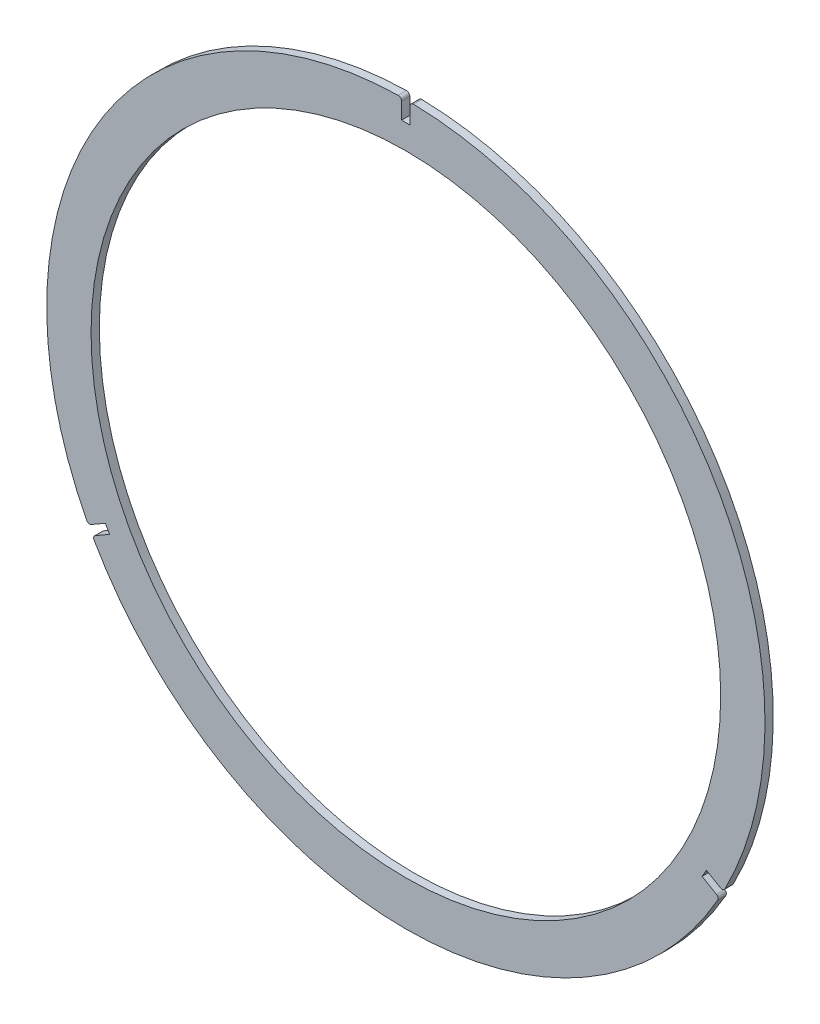
SolidWorks part; units mm, degrees
material "Balsa"
ref_plane "Front Plane" through (0, 0, 0) normal (0, 0, 1) x (1, 0, 0)
ref_plane "Top Plane" through (0, 0, 0) normal (0, 1, 0) x (1, 0, 0)
ref_plane "Right Plane" through (0, 0, 0) normal (1, 0, 0) x (0, 0, -1)
sketch "Sketch1" plane through (0, 0, 0) normal (0, 0, 1) x (1, 0, 0)
  line L0 (0, 0) -> (0, 499.9473) construction
  line L1 (0, -114.7984) -> (0, -129.4545) construction
  line L2 (0, -374.4718) -> (0, 404.2655) construction
  line L3 (-1.651, 142.9921) -> (-1.651, 150.6121)
  line L4 (1.651, 142.9921) -> (1.651, 150.6121)
  line L5 (-1.651, 142.9921) -> (1.651, 142.9921)
  line L6 (136.2041, -53.806) -> (0.0002, 24.7625) construction
  line L7 (-136.2076, -53.7991) -> (0.0002, 24.7625) construction
  line L8 (136.2041, -53.806) -> (0.0002, 24.7625) construction
  line L9 (-136.2076, -53.7991) -> (0.0002, 24.7625) construction
  line L10 (-125.0584, -45.4626) -> (-118.4576, -41.6554) construction
  line L11 (-123.6259, -48.4483) -> (-116.8078, -44.5157) construction
  line L12 (-118.4576, -41.6554) -> (-116.8078, -44.5157) construction
  line L13 (-124.1455, -48.7479) -> (-123.6847, -48.4822) construction
  line L14 (-123.6847, -48.4822) -> (-123.6259, -48.4483) construction
  line L15 (-125.7952, -45.8876) -> (-125.1113, -45.4931) construction
  line L16 (-125.1113, -45.4931) -> (-125.0584, -45.4626) construction
  line L17 (125.4797, -45.7137) -> (125.1075, -45.499) construction
  line L18 (123.8298, -48.5739) -> (123.6807, -48.488) construction
  line L19 (117.0223, -44.647) -> (118.6722, -41.7868) construction
  line L20 (123.6807, -48.488) -> (123.6228, -48.4545) construction
  line L21 (123.6228, -48.4545) -> (117.0223, -44.647) construction
  line L22 (125.1075, -45.499) -> (125.0554, -45.4689) construction
  line L23 (125.0554, -45.4689) -> (118.6722, -41.7868) construction
  line L24 (-115.3206, -47.981) -> (-121.8597, -51.7592)
  line L25 (-113.7312, -50.732) -> (-120.2754, -54.5131)
  line L26 (-113.7312, -50.732) -> (-120.2754, -54.5131) construction
  line L27 (-115.3206, -47.981) -> (-121.8597, -51.7592) construction
  line L28 (-115.4206, -47.9666) -> (-121.9445, -51.7361)
  line L29 (-120.2754, -54.5131) -> (-115.3206, -47.981) construction
  line L30 (-117.798, -51.2471) -> (-122.1124, -53.7399) construction
  line L31 (-113.7686, -50.8257) -> (-120.3665, -54.6379)
  line L32 (-115.4206, -47.9666) -> (-113.7686, -50.8257)
  line L33 (113.7316, -50.7396) -> (129.9098, -60.0883)
  line L34 (115.3212, -47.9888) -> (131.505, -57.3407)
  line L35 (129.9098, -60.0883) -> (131.505, -57.3407)
  line L36 (129.9098, -60.0883) -> (131.505, -57.3407) construction
  line L37 (115.3212, -47.9888) -> (131.505, -57.3407) construction
  line L38 (113.7316, -50.7396) -> (129.9098, -60.0883) construction
  line L39 (129.9098, -60.0883) -> (115.3212, -47.9888) construction
  line L40 (122.6155, -54.0385) -> (101.8722, -42.0519) construction
  line L41 (120.3631, -54.6438) -> (113.7655, -50.8313)
  line L42 (122.0152, -51.7848) -> (122.0057, -51.7794) construction
  line L43 (113.7655, -50.8313) -> (115.4176, -47.9723)
  line L44 (122.0057, -51.7794) -> (121.9413, -51.7421) construction
  line L45 (121.9413, -51.7421) -> (115.4176, -47.9723)
  line L48 (-115.3206, -47.981) -> (-113.7312, -50.732)
  line L49 (-115.3206, -47.981) -> (-113.7312, -50.732)
  line L51 (113.7316, -50.7396) -> (115.3212, -47.9888)
  line L52 (113.7316, -50.7396) -> (115.3212, -47.9888) construction
  arc A0 (-1.651, 150.6121) -> (-125.0584, -45.4626) centre (0, 12.7) ccw
  circle A1 centre (0, 12.7) radius 120.904
  arc A2 (0, 150.622) -> (-1.651, 150.6121) centre (0, 12.7) ccw construction
  circle A3 centre (0, 12.7) radius 137.922 construction
  arc A4 (1.651, 150.6121) -> (0, 150.622) centre (0, 12.7) ccw construction
  arc A5 (-124.3508, -46.9604) -> (-123.6259, -48.4483) centre (0, 12.7) ccw
  arc A6 (-123.6259, -48.4483) -> (-121.9445, -51.7361) centre (0, 12.7) ccw
  arc A7 (-125.0584, -45.4626) -> (-124.3508, -46.9604) centre (0, 12.7) ccw
  arc A8 (124.3477, -46.9667) -> (125.0554, -45.4689) centre (0, 12.7) ccw
  arc A9 (125.0554, -45.4689) -> (1.651, 150.6121) centre (0, 12.7) ccw
  arc A10 (123.6228, -48.4545) -> (124.3477, -46.9667) centre (0, 12.7) ccw
  arc A11 (-121.9153, -51.7914) -> (-121.1641, -53.1919) centre (0, 12.7) ccw construction
  arc A12 (-120.3665, -54.6379) -> (120.3631, -54.6438) centre (0, 12.7) ccw
  arc A13 (-121.9445, -51.7361) -> (-121.9153, -51.7914) centre (0, 12.7) ccw construction
  arc A14 (-121.1641, -53.1919) -> (-120.368, -54.6352) centre (0, 12.7) ccw construction
  arc A15 (-120.368, -54.6352) -> (-120.397, -54.5834) centre (0, 12.7) ccw construction
  arc A16 (-120.397, -54.5834) -> (-120.3665, -54.6379) centre (0, 12.7) ccw construction
  arc A17 (120.3936, -54.5893) -> (121.2977, -52.9456) centre (0, 12.7) ccw construction
  arc A18 (121.9413, -51.7421) -> (123.6228, -48.4545) centre (0, 12.7) ccw
  arc A19 (120.3631, -54.6438) -> (120.3936, -54.5893) centre (0, 12.7) ccw construction
  arc A20 (121.2977, -52.9456) -> (121.9121, -51.7974) centre (0, 12.7) ccw construction
  arc A21 (121.9121, -51.7974) -> (121.9413, -51.7421) centre (0, 12.7) ccw construction
  spline S1 degree 3 poles (-66.0123, 133.6164) (-70.0128, 131.4329) (-73.8716, 129.0699) (-81.3156, 123.9975) (-84.9009, 121.288) (-91.7995, 115.5249) (-95.113, 112.4712) (-99.0811, 108.4341) (-99.866, 107.6157) (-101.4182, 105.9565) (-102.1865, 105.1147) (-104.4569, 102.5643) (-105.9223, 100.8334) (-110.1768, 95.5512) (-115.4725, 88.2691) (-120.0285, 80.5179) (-123.1654, 74.5269) (-124.1643, 72.5002) (-125.5914, 69.415) (-126.0551, 68.3791) (-126.9587, 66.292) (-127.3989, 65.2397) (-129.5278, 59.9684) (-131.0098, 55.7) (-133.5456, 47.0638) (-134.5993, 42.696) (-136.2795, 33.8613) (-136.906, 29.3944) (-137.415, 23.7472) (-137.5031, 22.6146) (-137.6514, 20.3429) (-137.7116, 19.2049) (-137.8496, 15.7999) (-137.8852, 13.5361) (-137.8263, 6.7629) (-137.3062, -2.2197) (-135.9163, -11.1068) (-134.5433, -17.7359) (-134.0304, -19.9395) (-132.8922, -24.3345) (-132.2653, -26.5303) (-130.2347, -33.03) (-128.6774, -37.2656) (-126.1245, -43.2881) (-125.286, -45.1501) (-124.4066, -46.9926) knots 0 0 0 0 0.03125 0.03125 0.0625 0.0625 0.09375 0.09375 0.101563 0.101563 0.109375 0.109375 0.125 0.125 0.15625 0.1875 0.1875 0.203125 0.203125 0.210938 0.210938 0.21875 0.21875 0.25 0.25 0.28125 0.28125 0.3125 0.3125 0.320313 0.320313 0.328125 0.328125 0.34375 0.34375 0.375 0.40625 0.40625 0.421875 0.421875 0.4375 0.4375 0.46875 0.46875 0.48295 0.48295 0.48295 0.48295 construction
  spline S2 degree 3 poles (-1557.5256, 1030.3086) (-495.2142, -0.1753) (-82.1366, -210.7146) (81.4542, -98.9353) (85.033, -96.2237) (91.9188, -90.4573) (95.2258, -87.4025) (99.1858, -83.3647) (99.9691, -82.5461) (101.5182, -80.8868) (102.2849, -80.0449) (104.5506, -77.4941) (106.013, -75.7632) (110.2586, -70.4809) (112.9006, -66.8403) (117.8152, -59.3254) (120.0877, -55.4512) (123.2166, -49.4629) (124.2129, -47.4373) (125.6361, -44.3538) (126.0986, -43.3185) (126.9997, -41.2327) (127.4386, -40.181) (129.5618, -34.9121) (131.0396, -30.646) (133.5674, -22.0152) (134.6173, -17.6505) (136.2906, -8.8227) (136.914, -4.3596) (137.4197, 1.2823) (137.5071, 2.4139) (137.6542, 4.6834) (137.7138, 5.8206) (137.85, 9.2232) (137.8846, 11.4853) (137.8228, 18.2533) (137.2995, 27.2283) (135.9081, 36.1069) (134.5347, 42.7292) (134.0218, 44.9305) (132.8839, 49.3207) (132.2571, 51.5145) (130.2267, 58.0093) (128.67, 62.2416) (125.1615, 70.5162) (123.2097, 74.5586) (118.9108, 82.4534) (116.5637, 86.3058) (113.3753, 90.999) (112.7241, 91.9325) (111.3996, 93.7822) (110.7272, 94.697) (108.6802, 97.4113) (107.2757, 99.181) (102.9447, 104.3725) (96.8571, 110.9816) (90.1513, 116.9722) (84.8861, 121.2292) (83.0917, 122.6088) (80.3399, 124.6181) (79.4113, 125.2786) (77.543, 126.5731) (76.6028, 127.2075) (71.8708, 130.3161) (67.9881, 132.6004) (60.0328, 136.7739) (55.9603, 138.6631) (47.6249, 142.0446) (43.3619, 143.537) (37.9102, 145.1462) (36.8136, 145.4551) (34.6205, 146.0438) (33.5224, 146.3241) (30.2234, 147.1229) (28.0179, 147.5997) (21.3832, 148.8649) (16.9358, 149.4889) (7.993, 150.3014) (3.4975, 150.4899) (-3.2824, 150.4396) (-5.5486, 150.3672) (-10.0934, 150.1088) (-12.3559, 149.9236) (-19.101, 149.2046) (-23.5473, 148.5072) (-32.3412, 146.6856) (-36.6887, 145.5614) (-43.1354, 143.5526) (-45.2718, 142.8291) (-49.5193, 141.273) (-51.6323, 140.4395) (-274.1905, 46.1884) (-224.836, -608.7963) (101.1574, -1839.6029) knots -1.31339 -1.31339 -1.31339 -1.31339 0.03125 0.03125 0.0625 0.0625 0.09375 0.09375 0.101563 0.101563 0.109375 0.109375 0.125 0.125 0.15625 0.15625 0.1875 0.1875 0.203125 0.203125 0.210938 0.210938 0.21875 0.21875 0.25 0.25 0.28125 0.28125 0.3125 0.3125 0.320313 0.320313 0.328125 0.328125 0.34375 0.34375 0.375 0.40625 0.40625 0.421875 0.421875 0.4375 0.4375 0.46875 0.46875 0.5 0.5 0.53125 0.53125 0.539062 0.539062 0.546875 0.546875 0.5625 0.5625 0.59375 0.625 0.625 0.640625 0.640625 0.648437 0.648437 0.65625 0.65625 0.6875 0.6875 0.71875 0.71875 0.75 0.75 0.757812 0.757812 0.765625 0.765625 0.78125 0.78125 0.8125 0.8125 0.84375 0.84375 0.859375 0.859375 0.875 0.875 0.90625 0.90625 0.9375 0.9375 0.953125 0.953125 0.96875 0.96875 2.612134 2.612134 2.612134 2.612134 only from (66.1767, -108.566) to (-66.0123, 133.6164)
  spline S3 degree 3 poles (66.1767, -108.566) (70.1708, -106.3789) (74.0231, -104.0129) (81.4542, -98.9353) (85.033, -96.2237) (91.9188, -90.4573) (95.2258, -87.4025) (99.1858, -83.3647) (99.9691, -82.5461) (101.5182, -80.8868) (102.2849, -80.0449) (104.5506, -77.4941) (106.013, -75.7632) (110.2586, -70.4809) (112.9006, -66.8403) (117.8152, -59.3254) (120.0877, -55.4512) (123.2166, -49.4629) (124.2129, -47.4373) (125.6361, -44.3538) (126.0986, -43.3185) (126.9997, -41.2327) (127.4386, -40.181) (129.5618, -34.9121) (131.0396, -30.646) (133.5674, -22.0152) (134.6173, -17.6505) (136.2906, -8.8227) (136.914, -4.3596) (137.4197, 1.2823) (137.5071, 2.4139) (137.6542, 4.6834) (137.7138, 5.8206) (137.85, 9.2232) (137.8846, 11.4853) (137.8228, 18.2533) (137.2995, 27.2283) (135.9081, 36.1069) (134.5347, 42.7292) (134.0218, 44.9305) (132.8839, 49.3207) (132.2571, 51.5145) (130.2267, 58.0093) (128.67, 62.2416) (125.1615, 70.5162) (123.2097, 74.5586) (118.9108, 82.4534) (116.5637, 86.3058) (113.3753, 90.999) (112.7241, 91.9325) (111.3996, 93.7822) (110.7272, 94.697) (108.6802, 97.4113) (107.2757, 99.181) (102.9447, 104.3725) (96.8571, 110.9816) (90.1513, 116.9722) (84.8861, 121.2292) (83.0917, 122.6088) (80.3399, 124.6181) (79.4113, 125.2786) (77.543, 126.5731) (76.6028, 127.2075) (71.8708, 130.3161) (67.9881, 132.6004) (60.0328, 136.7739) (55.9603, 138.6631) (47.6249, 142.0446) (43.3619, 143.537) (37.9102, 145.1462) (36.8136, 145.4551) (34.6205, 146.0438) (33.5224, 146.3241) (30.2234, 147.1229) (28.0179, 147.5997) (21.3832, 148.8649) (16.9358, 149.4889) (7.993, 150.3014) (3.4975, 150.4899) (-3.2824, 150.4396) (-5.5486, 150.3672) (-10.0934, 150.1088) (-12.3559, 149.9236) (-19.101, 149.2046) (-23.5473, 148.5072) (-32.3412, 146.6856) (-36.6887, 145.5614) (-43.1354, 143.5526) (-45.2718, 142.8291) (-49.5193, 141.273) (-51.6323, 140.4395) (-57.9206, 137.7764) (-62.0153, 135.798) (-66.0123, 133.6164) knots 0 0 0 0 0.03125 0.03125 0.0625 0.0625 0.09375 0.09375 0.101563 0.101563 0.109375 0.109375 0.125 0.125 0.15625 0.15625 0.1875 0.1875 0.203125 0.203125 0.210938 0.210938 0.21875 0.21875 0.25 0.25 0.28125 0.28125 0.3125 0.3125 0.320313 0.320313 0.328125 0.328125 0.34375 0.34375 0.375 0.40625 0.40625 0.421875 0.421875 0.4375 0.4375 0.46875 0.46875 0.5 0.5 0.53125 0.53125 0.539062 0.539062 0.546875 0.546875 0.5625 0.5625 0.59375 0.625 0.625 0.640625 0.640625 0.648437 0.648437 0.65625 0.65625 0.6875 0.6875 0.71875 0.71875 0.75 0.75 0.757812 0.757812 0.765625 0.765625 0.78125 0.78125 0.8125 0.8125 0.84375 0.84375 0.859375 0.859375 0.875 0.875 0.90625 0.90625 0.9375 0.9375 0.953125 0.953125 0.96875 0.96875 1 1 1 1 construction
  spline S4 degree 3 poles (-124.4066, -46.9926) (-124.169, -47.4906) (-123.9283, -47.9871) (-123.6847, -48.4822) knots 0.48295 0.48295 0.48295 0.48295 0.486788 0.486788 0.486788 0.486788 construction
  spline S5 degree 3 poles (-123.6847, -48.4822) (-122.846, -50.1865) (-121.9718, -51.874) (-118.9108, -57.4955) (-116.5612, -61.3517) (-113.369, -66.0497) (-112.7169, -66.9844) (-111.3913, -68.8351) (-110.7184, -69.7503) (-108.6697, -72.4662) (-107.264, -74.2369) (-102.929, -79.4315) (-96.8353, -86.0447) (-90.1214, -92.0392) (-84.8493, -96.299) (-83.0524, -97.6795) (-80.2967, -99.6899) (-79.367, -100.3507) (-77.4971, -101.6451) (-76.5559, -102.2795) (-71.8198, -105.3881) (-67.9332, -107.6723) (-59.9695, -111.8452) (-55.8924, -113.7339) (-47.5468, -117.114) (-43.2782, -118.6053) (-37.8188, -120.2127) (-36.7216, -120.521) (-34.5268, -121.1085) (-33.4279, -121.3881) (-30.1264, -122.185) (-27.9191, -122.6605) (-21.2788, -123.9216) (-16.8274, -124.5426) (-7.8757, -125.3484) (-3.3755, -125.5332) (3.4122, -125.4766) (5.6812, -125.4019) (10.231, -125.1387) (12.493, -124.9512) (19.2413, -124.2249) (23.6899, -123.5224) (32.4889, -121.6898) (36.8393, -120.5597) (43.2904, -118.5412) (45.4283, -117.8143) (48.6163, -116.6419) (49.6759, -116.2374) (51.7885, -115.4006) (52.8426, -114.968) (58.0839, -112.7404) (62.1792, -110.755) (66.1767, -108.566) knots 0.486788 0.486788 0.486788 0.486788 0.5 0.5 0.53125 0.53125 0.539062 0.539062 0.546875 0.546875 0.5625 0.5625 0.59375 0.625 0.625 0.640625 0.640625 0.648437 0.648437 0.65625 0.65625 0.6875 0.6875 0.71875 0.71875 0.75 0.75 0.757812 0.757812 0.765625 0.765625 0.78125 0.78125 0.8125 0.8125 0.84375 0.84375 0.859375 0.859375 0.875 0.875 0.90625 0.90625 0.9375 0.9375 0.953125 0.953125 0.960937 0.960937 0.96875 0.96875 1 1 1 1 construction
  spline S6 degree 3 poles (-2106.0787, 3411.0956) (-795.1258, 1114.0107) (536.096, -1200.0633) (1875.8445, -3510.6921) knots -1262.072517 -1262.072517 -1262.072517 -1262.072517 1256.953485 1256.953485 1256.953485 1256.953485 weights 1.002223 0.999266 0.999259 1.002202 only from (-121.8597, -51.7592) to (-120.2754, -54.5131)
  spline S7 degree 3 poles (-121.0676, -53.1362) (-120.8035, -53.5952) (-120.5395, -54.0542) (-120.2754, -54.5131) knots 0.5 0.5 0.5 0.5 1 1 1 1 weights 1 1 1 1 construction
  spline S9 degree 3 poles (-121.8597, -51.7592) (-121.5957, -52.2182) (-121.3316, -52.6772) (-121.0676, -53.1362) knots 0 0 0 0 0.5 0.5 0.5 0.5 weights 1 1 1 1 construction
  point P7 (0, -125.5003)
  point P8 (0, 150.4602)
  point P25 (-125.0584, -45.4626)
  point P38 (123.6228, -48.4545)
  dimension "D1" = 275.9605
  dimension "D2" = 275.844
  dimension "D3" = 12.7
  dimension "D5" = 3.302
  dimension "D6" = 7.62
  dimension "D7" = 3.302
  dimension "D8" = 7.62
  dimension "D9" = 3.302
  dimension "D10" = 7.62
  dimension "D11" = 3.302
  dimension "D12" = 7.62
  dimension "D13" = 3.302
  dimension "D14" = 7.62
  dimension "D4" = 17.018
extrude "Boss-Extrude1" add sketch "Sketch1" along normal mid plane 3.175
fillet "Fillet1" radius 1.27 6 edges at (-121.9445, -51.7361, 0) (-120.3665, -54.6379, 0) (121.9413, -51.7421, 0) (120.3631, -54.6438, 0) (1.651, 150.6121, 0) (-1.651, 150.6121, 0)
